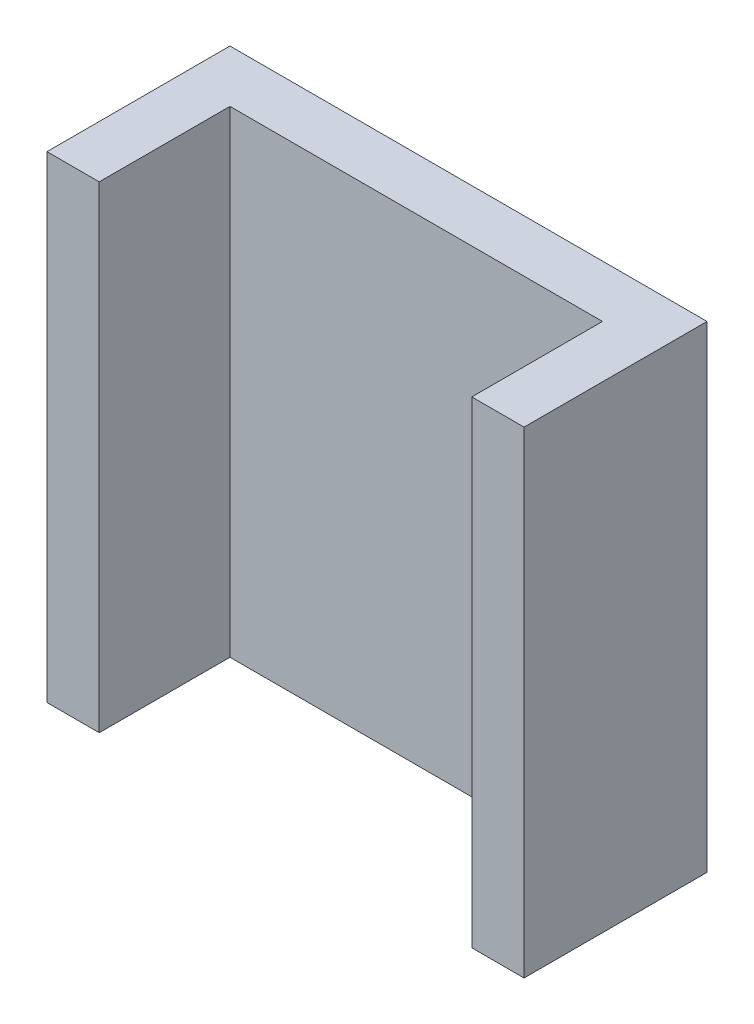
SolidWorks part; units mm, degrees
ref_plane "Plan de face" through (0, 0, 0) normal (0, 0, 1) x (1, 0, 0)
ref_plane "Plan de dessus" through (0, 0, 0) normal (0, 1, 0) x (1, 0, 0)
ref_plane "Plan de droite" through (0, 0, 0) normal (1, 0, 0) x (0, 0, -1)
sketch "Esquisse1" plane through (0, 0, 0) normal (0, 0, 1) x (1, 0, 0)
  line L1 (0, 0) -> (73, 0)
  line L2 (0, 0) -> (0, 73)
  line L3 (0, 73) -> (73, 73)
  line L4 (73, 0) -> (73, 73)
  dimension "D1" = 73
  dimension "D2" = 73
extrude "Boss.-Extru.1" add sketch "Esquisse1" along normal blind 8
sketch "Esquisse2" plane through (0, 0, 8) normal (0, 0, 1) x (1, 0, 0)
  line L4 (73, 73) -> (0, 73) construction
  line L6 (8, 73) -> (8, 0)
  line L8 (0, 73) -> (0, 0)
  line L9 (0, 0) -> (73, 0)
  line L10 (73, 0) -> (73, 73)
  line L11 (73, 73) -> (0, 73)
  line L12 (0, 73) -> (0, 0)
  line L13 (0, 0) -> (8, 0)
  line L14 (73, 0) -> (73, 73)
  line L15 (73, 73) -> (65, 73)
  line L16 (65, 73) -> (65, 0)
  line L17 (0, 0) -> (73, 0) construction
  line L18 (8, 73) -> (0, 73)
  line L19 (65, 0) -> (73, 0)
  point P6 (8, 73)
  point P11 (8, 8)
  point P12 (8, 0)
  point P15 (65, 0)
  point P16 (65, 73)
  dimension "D4" = 8
  dimension "D5" = 8
  dimension "D1" = 0
extrude "Boss.-Extru.2" add sketch "Esquisse2" along normal blind 20
equation "\"epaiss_cadre\"= 8"
equation "\"D2@Esquisse1\"=\"epaiss_cadre\"+65"
equation "\"D1@Esquisse1\"=\"epaiss_cadre\"+65"
equation "\"D1@Boss.-Extru.1\"=\"epaiss_cadre\""
equation "\"D4@Esquisse2\"=\"epaiss_cadre\""
equation "\"D5@Esquisse2\"=\"epaiss_cadre\""
